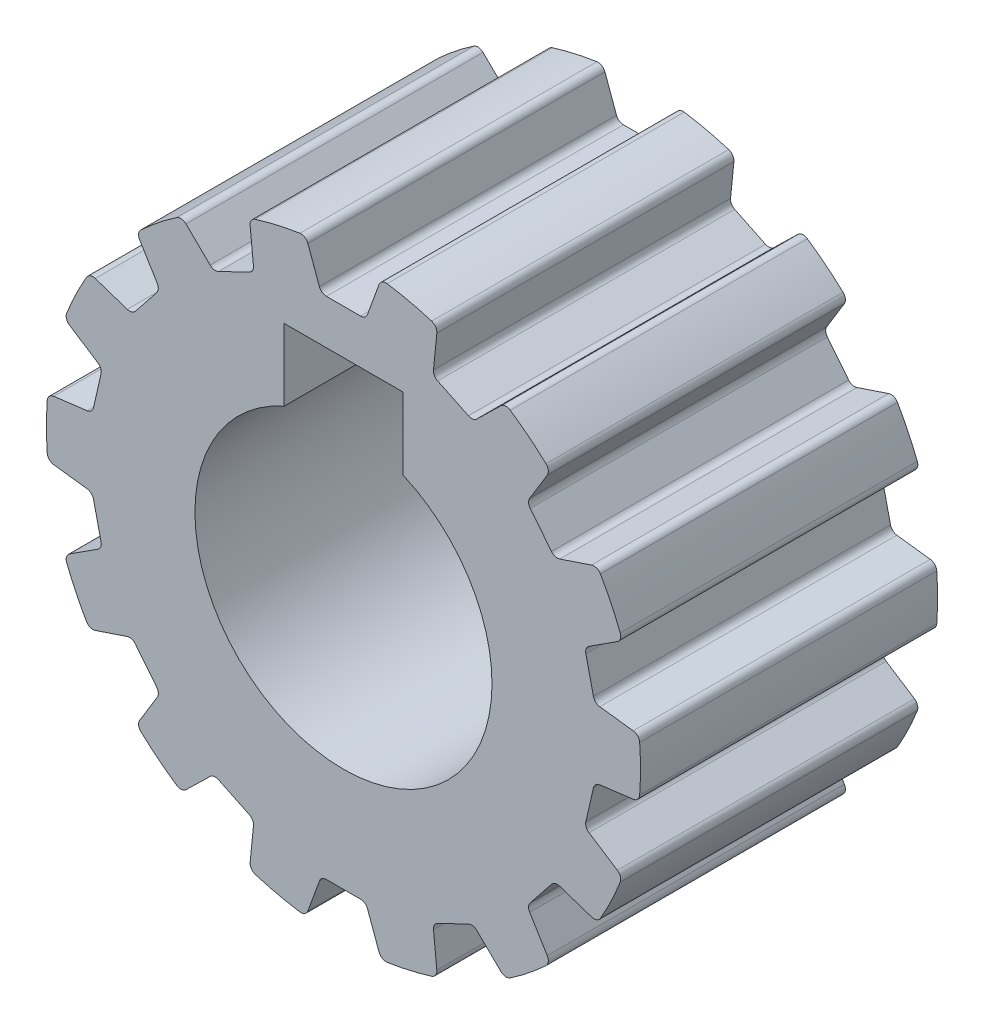
SolidWorks part; units mm, degrees
material "Alloy Steel (SS)"
ref_plane "Front " through (0, 0, 0) normal (0, 0, 1) x (1, 0, 0)
ref_plane "Top " through (0, 0, 0) normal (0, 1, 0) x (1, 0, 0)
ref_plane "Right " through (0, 0, 0) normal (1, 0, 0) x (0, 0, -1)
sketch "Sketch1" plane through (0, 0, 0) normal (0, 0, 1) x (1, 0, 0)
  line L0 (0, 0) -> (0, 8.2956) construction
  line L2 (2, 7) -> (-2, 7)
  line L3 (2, 7) -> (2, 4.5826)
  line L5 (-2, 7) -> (-2, 4.5826)
  circle A0 centre (0, 0) radius 10
  arc A1 (-2, 4.5826) -> (2, 4.5826) centre (0, 0) ccw
  dimension "D1" = 20
  dimension "D2" = 10
  dimension "D3" = 4
  dimension "D4" = 7
extrude "Boss-Extrude1" add sketch "Sketch1" along normal blind 10
sketch "Sketch2" plane through (0, 0, 10) normal (0, 0, 1) x (1, 0, 0)
  line L0 (0, 0) -> (0, 10) construction
  line L1 (-0.75, 8.5) -> (0.75, 8.5)
  line L2 (0.75, 8.5) -> (1.2666, 9.9195)
  line L3 (-0.75, 8.5) -> (-1.2666, 9.9195)
  circle A0 centre (0, 0) radius 10 construction
  circle A1 centre (0, 0) radius 10
  circle M5 centre (0, 0) radius 10
  dimension "D1" = 1.5
  dimension "D2" = 20
  dimension "D3" = 20
  dimension "D4" = 8.5
extrude "Cut-Extrude1" cut sketch "Sketch2" against normal through all contours L1 L0 A1 L3 | L0 L1 L2 M5
pattern_circular "CirPattern1" count 14 over 360 about axis through (0, 0, 0) along (0, 0, 1) of "Cut-Extrude1"
fillet "Fillet1" radius 0.25 56 edges at (5.4451, 8.3875, 5) (4.3637, 7.3328, 5) (3.0123, 7.9836, 5) (3.1627, 9.4867, 5) (1.2666, 9.9195, 5) (0.75, 8.5, 5) (-0.75, 8.5, 5) (-1.2666, 9.9195, 5) (-3.1627, 9.4867, 5) (-3.0123, 7.9836, 5) (-4.3637, 7.3328, 5) (-5.4451, 8.3875, 5) (-6.9656, 7.175, 5) (-6.178, 5.886, 5) (-7.1132, 4.7133, 5) (-8.5451, 5.1944, 5) (-9.3889, 3.4422, 5) (-8.12, 2.6226, 5) (-8.4538, 1.1602, 5) (-9.9526, 0.9724, 5) (-9.9526, -0.9724, 5) (-8.4538, -1.1602, 5) (-8.12, -2.6226, 5) (-9.3889, -3.4422, 5) (-8.5451, -5.1944, 5) (-7.1132, -4.7133, 5) (-6.178, -5.886, 5) (-6.9656, -7.175, 5) (-5.4451, -8.3875, 5) (-4.3637, -7.3328, 5) (-3.0123, -7.9836, 5) (-3.1627, -9.4867, 5) (-1.2666, -9.9195, 5) (-0.75, -8.5, 5) (0.75, -8.5, 5) (1.2666, -9.9195, 5) (3.1627, -9.4867, 5) (3.0123, -7.9836, 5) (4.3637, -7.3328, 5) (5.4451, -8.3875, 5) (6.9656, -7.175, 5) (6.178, -5.886, 5) (7.1132, -4.7133, 5) (8.5451, -5.1944, 5) (9.3889, -3.4422, 5) (8.12, -2.6226, 5) (8.4538, -1.1602, 5) (9.9526, -0.9724, 5) (9.9526, 0.9724, 5) (8.4538, 1.1602, 5) (8.12, 2.6226, 5) (9.3889, 3.4422, 5) (8.5451, 5.1944, 5) (7.1132, 4.7133, 5) (6.178, 5.886, 5) (6.9656, 7.175, 5)
